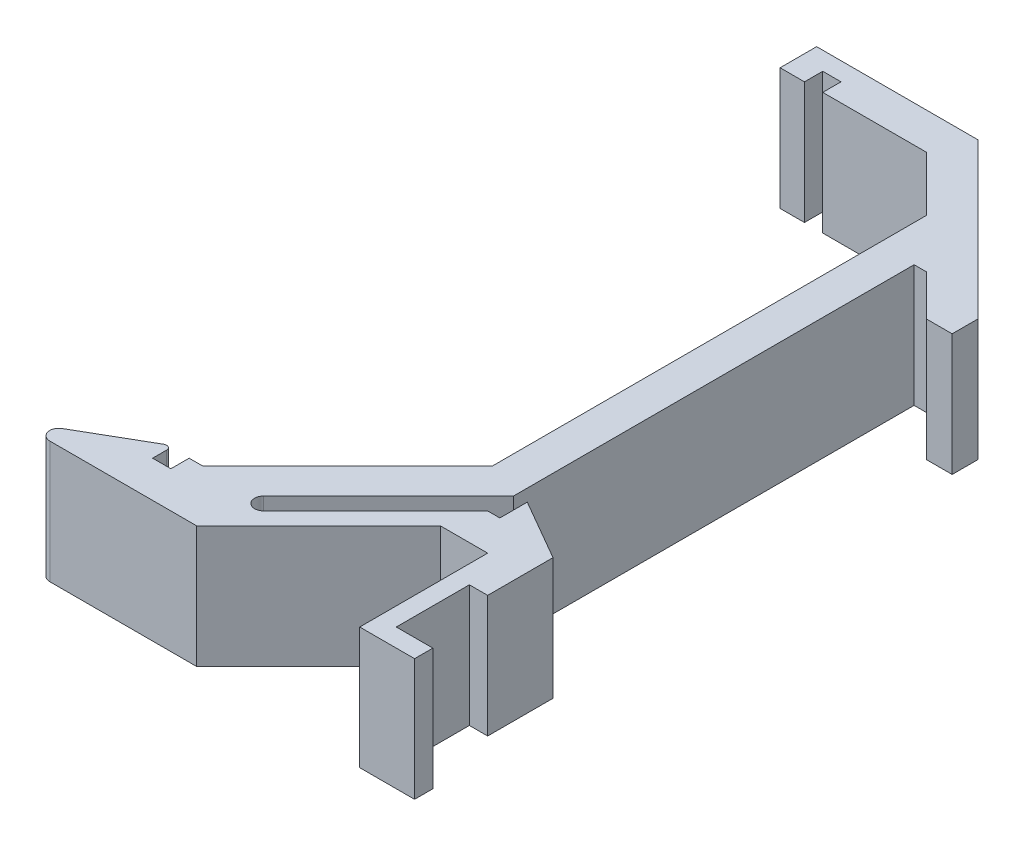
SolidWorks part; units mm, degrees
ref_plane "Спереди" through (0, 0, 0) normal (0, 0, 1) x (1, 0, 0)
ref_plane "Сверху" through (0, 0, 0) normal (0, 1, 0) x (1, 0, 0)
ref_plane "Справа" through (0, 0, 0) normal (1, 0, 0) x (0, 0, -1)
sketch "Эскиз2" plane through (0, 0, 0) normal (0, 1, 0) x (1, 0, 0)
  line L0 (-12.853, -2.5775) -> (-12.853, -4.0775)
  line L1 (-12.853, -4.0775) -> (-14.353, -4.0775)
  line L2 (-14.353, -4.0775) -> (-14.353, -2.9275)
  line L3 (-14.878, -2.6244) -> (-20.167, -5.678)
  line L4 (-19.792, -7.0775) -> (-7.7317, -7.0775)
  line L5 (-14.703, -2.5775) -> (-12.853, -2.5775) construction
  line L6 (-12.853, 49.4225) -> (-12.853, 50.9225)
  line L7 (-12.853, 50.9225) -> (-14.353, 50.9225)
  line L8 (-14.353, 50.9225) -> (-14.353, 49.4225)
  line L9 (-14.353, 49.4225) -> (-16.353, 49.4225)
  line L10 (-16.353, 49.4225) -> (-16.353, 52.4225)
  line L11 (-16.353, 52.4225) -> (-3.1104, 52.4225)
  line L12 (-12.853, 49.4225) -> (-4.353, 49.4225)
  line L13 (-4.353, 49.4225) -> (0.147, 44.9225)
  line L14 (0.147, 44.9225) -> (0.147, 9.2864)
  line L15 (0.147, 9.2864) -> (-11.717, -2.5775)
  line L16 (-12.853, -2.5775) -> (-11.717, -2.5775)
  line L17 (-3.1104, 52.4225) -> (9.6175, 39.6946)
  line L18 (3.147, 8.0438) -> (3.147, 40.9225)
  line L19 (3.147, 40.9225) -> (4.147, 40.9225)
  line L20 (4.147, 40.9225) -> (7.4962, 37.5732)
  line L21 (9.6175, 39.6946) -> (9.6175, 37.5732)
  line L22 (9.6175, 37.5732) -> (7.4962, 37.5732)
  line L23 (10.647, -7.5775) -> (6.147, -7.5775)
  line L24 (6.147, -7.5775) -> (6.147, 2.9225)
  line L25 (6.147, 2.9225) -> (2.2683, 2.9225)
  line L26 (2.2683, 2.9225) -> (-7.7317, -7.0775)
  line L27 (10.647, -7.5775) -> (10.647, -6.0775)
  line L28 (10.647, -6.0775) -> (7.647, -6.0775)
  line L29 (7.647, -6.0775) -> (7.647, -0.0775)
  line L30 (7.647, -0.0775) -> (9.147, -0.0775)
  line L31 (9.147, -0.0775) -> (9.147, 5.2857)
  line L32 (9.147, 5.2857) -> (4.147, 8.1725)
  line L33 (4.147, 8.1725) -> (4.147, 5.9225)
  line L34 (4.147, 5.9225) -> (3.147, 5.9225)
  line L35 (3.147, 5.9225) -> (-6.0454, -3.2699)
  line L36 (3.147, 5.9225) -> (3.147, 8.0438) construction
  line L37 (3.647, 40.9225) -> (3.647, 5.9225) construction
  line L38 (-7.0919, -3.2699) -> (-7.1061, -3.2558)
  line L39 (-7.1061, -2.2092) -> (3.147, 8.0438)
  arc A0 (-20.167, -5.678) -> (-19.792, -7.0775) centre (-19.792, -6.3275) ccw
  arc A1 (-14.353, -2.9275) -> (-14.878, -2.6244) centre (-14.703, -2.9275) ccw
  arc A2 (-6.0454, -3.2699) -> (-7.0919, -3.2699) centre (-6.5687, -2.7466) cw
  arc A3 (-7.1061, -3.2558) -> (-7.1061, -2.2092) centre (-6.5828, -2.7325) cw
  point P48 (3.647, 23.4225)
  dimension "D4" = 0.75
  dimension "D5" = 0.35
  dimension "D31" = 0.74
  dimension "D1" = 1.5
  dimension "D3" = 4.5
  dimension "D6" = 3
  dimension "D7" = 55
  dimension "D8" = 3
  dimension "D9" = 3
  dimension "D10" = 45
  dimension "D11" = 1
  dimension "D12" = 18
  dimension "D13" = 16
  dimension "D14" = 4.5
  dimension "D15" = 1.5
  dimension "D16" = 6
  dimension "D17" = 3
  dimension "D18" = 10.5
  dimension "D19" = 3
  dimension "D20" = 1.5
  dimension "D21" = 1.5
  dimension "D22" = 240
  dimension "D23" = 1
  dimension "D24" = 1.5
  dimension "D25" = 135
  dimension "D26" = 2.25
  dimension "D27" = 6
  dimension "D28" = 35
  dimension "D29" = 27.5
  dimension "D30" = 1.5
  dimension "D32" = 13
  dimension "D33" = 27.5
  dimension "D34" = 2
  dimension "D36" = 30
extrude "Бобышка-Вытянуть2" add sketch "Эскиз2" along normal blind 10
